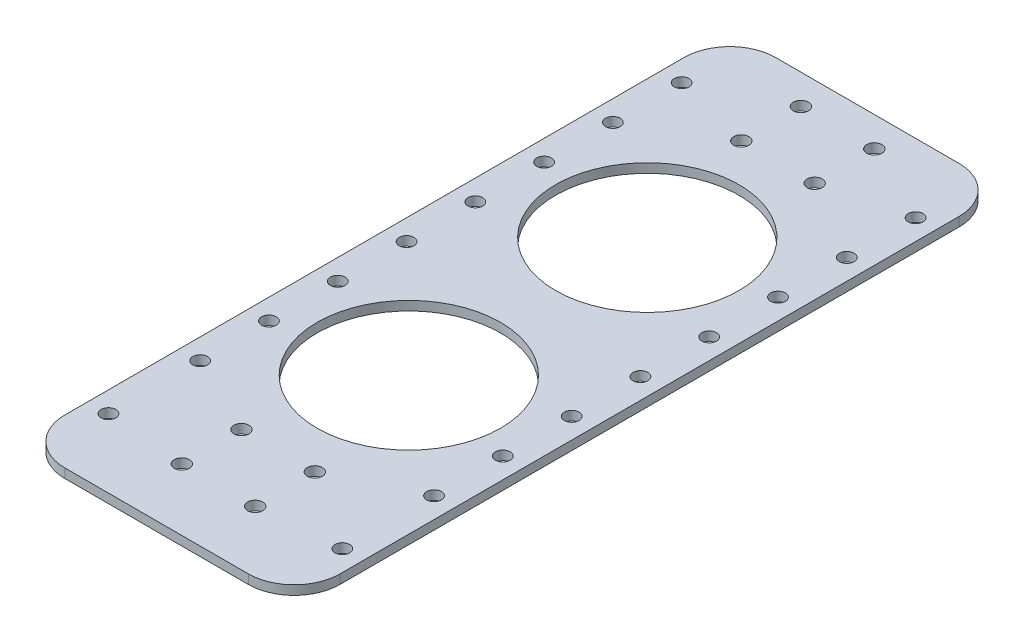
SolidWorks part; units mm, degrees
material "PET"
ref_plane "前视基准面" through (0, 0, 0) normal (0, 0, 1) x (1, 0, 0)
ref_plane "上视基准面" through (0, 0, 0) normal (0, 1, 0) x (1, 0, 0)
ref_plane "右视基准面" through (0, 0, 0) normal (1, 0, 0) x (0, 0, -1)
other "Configuration Table"
sketch "草图1" plane through (0, 0, 0) normal (0, 1, 0) x (1, 0, 0)
  line L1 (-30, 40) -> (30, 40)
  line L2 (-30, 40) -> (-30, -40)
  line L3 (-30, -40) -> (30, -40)
  line L4 (30, 40) -> (30, -40)
  line L5 (-30, 40) -> (30, -40) construction
  line L6 (-30, -40) -> (30, 40) construction
  point P0 (0, 0)
  dimension "D1" = 60
  dimension "D2" = 80
extrude "凸台-拉伸1" add sketch "草图1" along normal blind 2
sketch "草图2" plane through (0, 2, 0) normal (0, 1, 0) x (1, 0, 0)
  line L0 (0, 0) -> (0, -40) construction
  line L1 (-30, -40) -> (30, -40) construction
  circle A0 centre (0, -20) radius 9.4993 construction
  circle A1 centre (0, -10.5007) radius 1.4
  circle A3 centre (9.4993, -20) radius 1.4
  circle A4 centre (0, -29.4993) radius 1.4
  circle A5 centre (-9.4993, -20) radius 1.4
  point P18 (0, -20)
  dimension "D1" = 18.9986
  dimension "D2" = 2.8
  dimension "D3" = 4
extrude "切除-拉伸1" cut sketch "草图2" against normal blind 50
sketch "草图3" plane through (0, 2, 0) normal (0, 1, 0) x (1, 0, 0)
  line L0 (-9.4993, -20) -> (9.4993, -20) construction
  circle A0 centre (0, -20) radius 2
  dimension "D1" = 4
extrude "切除-拉伸2" cut sketch "草图3" against normal blind 50
sketch "草图5" plane through (0, 2, 0) normal (0, 1, 0) x (1, 0, 0)
  line L1 (-30, 40) -> (30, 40)
  line L2 (-30, 40) -> (-30, 80)
  line L3 (-30, 80) -> (30, 80)
  line L4 (30, 40) -> (30, 80)
  dimension "D1" = 40
extrude "凸台-拉伸2" add sketch "草图5" against normal up to surface (2 mm away) up to face at (0, 0, 22)
sketch "草图6" plane through (0, 2, 0) normal (0, 1, 0) x (1, 0, 0)
  line L0 (-30, 80) -> (-30, -40) construction
  circle A0 centre (0, 32) radius 20
  circle A1 centre (0, -20) radius 2 construction
  dimension "D1" = 52
  dimension "D2" = 40
  dimension "D3" = 30
extrude "切除-拉伸4" cut sketch "草图6" against normal blind 50
sketch "草图4" plane through (0, 2, 0) normal (0, 1, 0) x (1, 0, 0)
  line L0 (0, 40) -> (0, 0) construction
  line L3 (-8, 60.5) -> (8, 60.5) construction
  line L4 (-8, 60.5) -> (-8, 73.5) construction
  line L5 (-8, 73.5) -> (8, 73.5) construction
  line L6 (8, 60.5) -> (8, 73.5) construction
  line L7 (-8, 60.5) -> (8, 73.5) construction
  line L8 (-8, 73.5) -> (8, 60.5) construction
  circle A0 centre (-8, 73.5) radius 1.65
  circle A1 centre (8, 73.5) radius 1.65
  circle A2 centre (8, 60.5) radius 1.65
  circle A3 centre (-8, 60.5) radius 1.65
  circle A4 centre (0, 32) radius 20 construction
  point P5 (0, 67)
  dimension "D3" = 3.3
  dimension "D4" = 3.3
  dimension "D5" = 3.3
  dimension "D6" = 3.3
  dimension "D7" = 28.5
  dimension "D1" = 16
  dimension "D2" = 13
extrude "切除-拉伸3" cut sketch "草图4" against normal blind 50
sketch "草图7" plane through (0, 2, 0) normal (0, 1, 0) x (1, 0, 0)
  line L0 (-30, 80) -> (-25.5, 80) construction
  line L1 (30, 80) -> (-30, 80) construction
  line L2 (-25.5, 80) -> (-25.5, -40) construction
  line L3 (-30, -40) -> (30, -40) construction
  line L4 (-25.5, 20) -> (-25.5, 5) construction
  line L5 (-25.5, 20) -> (-25.5, 35) construction
  line L6 (0, 80) -> (0, -40) construction
  line L7 (25.5, 20) -> (25.5, 35) construction
  line L8 (25.5, 20) -> (25.5, 5) construction
  circle A0 centre (-25.5, 20) radius 1.6
  circle A1 centre (-25.5, 5) radius 1.6
  circle A2 centre (-25.5, -10) radius 1.6
  circle A3 centre (-25.5, -25) radius 1.6
  circle A4 centre (-25.5, 35) radius 1.6
  circle A5 centre (-25.5, 50) radius 1.6
  circle A6 centre (-25.5, 65) radius 1.6
  circle A7 centre (25.5, 65) radius 1.6
  circle A8 centre (25.5, 50) radius 1.6
  circle A9 centre (25.5, 35) radius 1.6
  circle A10 centre (25.5, -25) radius 1.6
  circle A11 centre (25.5, -10) radius 1.6
  circle A12 centre (25.5, 5) radius 1.6
  circle A13 centre (25.5, 20) radius 1.6
  dimension "D2" = 3.2
  dimension "D1" = 4.5
  dimension "D4" = 15
  dimension "D6" = 15
  dimension "D3" = 4
  dimension "D5" = 4
extrude "切除-拉伸5" cut sketch "草图7" against normal blind 10
sketch "草图9" plane through (0, 2, 0) normal (0, 1, 0) x (1, 0, 0)
  line L0 (-25.5, 5) -> (-25.5, -10) construction
  line L1 (-25.5, -10) -> (25.5, -10) construction
  line L6 (25.5, -10) -> (25.5, 5) construction
  line L7 (25.5, 5) -> (-25.5, 5) construction
  line L8 (21.5, 1) -> (-21.5, 1)
  line L9 (-21.5, 1) -> (-21.5, -6)
  line L10 (-21.5, -6) -> (21.5, -6)
  line L11 (21.5, -6) -> (21.5, 1)
  point P4 (0, 5)
  dimension "D1" = 4
sketch "草图11" plane through (0, 2, 0) normal (0, 1, 0) x (1, 0, 0)
  line L0 (30, -40) -> (30, 80) construction
  line L1 (-30, -40) -> (30, -40)
  line L2 (-30, -40) -> (-30, -75)
  line L3 (-30, -75) -> (30, -75)
  line L4 (30, -40) -> (30, -75)
  dimension "D1" = 0
  dimension "D2" = 35
extrude "凸台-拉伸3" add sketch "草图11" against normal up to surface (2 mm away) up to face at (-25.5, 0, -33.4)
sketch "草图12" plane through (0, 2, 0) normal (0, 1, 0) x (1, 0, 0)
  line L0 (0, 32) -> (0, -20) construction
  line L1 (0, 6) -> (30, 6) construction
  line L2 (30, -75) -> (30, 80) construction
ref_plane "基准面1" through (0, 0, -6) normal (0, 0, 1) x (1, 0, 0)
mirror "镜向2" about plane through (0, 0, -6) normal (0, 0, 1) of "切除-拉伸3", "切除-拉伸4"
fillet "圆角1" radius 10 4 edges at (-30, 1, -80) (30, 1, -80) (30, 1, 75) (-30, 1, 75)
sketch "草图13" plane through (0, 0, 0) normal (0, -1, 0) x (-1, 0, 0)
  line L0 (-25.5, -25) -> (-25.5, -70) construction
  line L1 (-20, -75) -> (20, -75) construction
  line L2 (0, -75) -> (0, -40) construction
  circle A0 centre (-25.5, -60) radius 1.6
  circle A2 centre (0, -20) radius 20 construction
  circle A3 centre (25.5, -60) radius 1.6
  dimension "D1" = 15
  dimension "D2" = 3.2
extrude "切除-拉伸6" cut sketch "草图13" against normal blind 10
sketch "草图14" plane through (0, 2, 0) normal (0, 1, 0) x (1, 0, 0)
  circle A0 centre (-25.5, 5) radius 1.6
  circle A1 centre (-25.5, -10) radius 1.6
  circle A2 centre (25.5, 5) radius 1.6
  circle A3 centre (25.5, -10) radius 1.6
sketch "草图17" plane through (0, 2, 0) normal (0, 1, 0) x (1, 0, 0)
  line L0 (-25.5, -25) -> (-25.5, -40) construction
  line L1 (25.5, -25) -> (25.5, -40) construction
  circle A0 centre (-25.5, -40) radius 1.6
  circle A1 centre (25.5, -40) radius 1.6
  dimension "D2" = 3.2
  dimension "D1" = 15
extrude "切除-拉伸7" cut sketch "草图17" against normal blind 10
